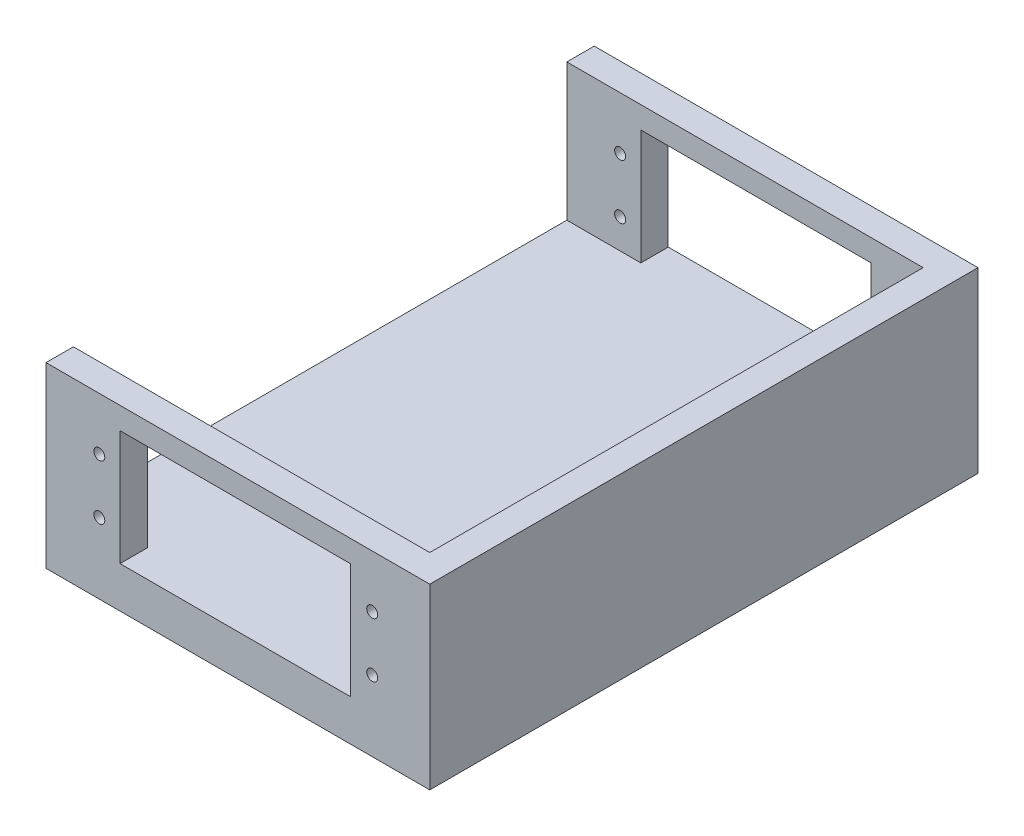
SolidWorks part; units mm, degrees
material "ABS"
ref_plane "Front Plane" through (0, 0, 0) normal (0, 0, 1) x (1, 0, 0)
ref_plane "Top Plane" through (0, 0, 0) normal (0, 1, 0) x (1, 0, 0)
ref_plane "Right Plane" through (0, 0, 0) normal (1, 0, 0) x (0, 0, -1)
sketch "Sketch1" plane through (0, 0, 0) normal (0, 1, 0) x (1, 0, 0)
  line L1 (0, 0) -> (70, 0)
  line L2 (0, 0) -> (0, 50)
  line L3 (0, 50) -> (70, 50)
  line L4 (70, 0) -> (70, 50)
  dimension "D1" = 70
  dimension "D2" = 50
extrude "Boss-Extrude1" add sketch "Sketch1" along normal blind 7.5
sketch "Sketch2" plane through (0, 7.5, 0) normal (0, 1, 0) x (1, 0, 0)
  line L0 (0, 50) -> (0, 0) construction
  line L1 (0, 0) -> (70, 0)
  line L2 (0, 0) -> (0, 5)
  line L3 (0, 5) -> (70, 5)
  line L4 (70, 0) -> (70, 5)
  line L5 (70, 0) -> (70, 50) construction
  line L6 (0, 0) -> (70, 0) construction
  dimension "D1" = 5
  dimension "D2" = 0
extrude "Boss-Extrude2" add sketch "Sketch2" along normal blind 25
sketch "Sketch3" plane through (0, 0, 0) normal (0, 0, 1) x (1, 0, 0)
  line L4 (13.5, 28.5) -> (55.5, 28.5)
  line L5 (13.5, 28.5) -> (13.5, 7.5)
  line L6 (13.5, 7.5) -> (55.5, 7.5)
  line L7 (55.5, 28.5) -> (55.5, 7.5)
  line L8 (0, 0) -> (70, 0) construction
  line L10 (70, 32.5) -> (70, 0) construction
  circle A4 centre (9.7208, 22.9) radius 1
  circle A5 centre (9.7208, 12.9) radius 1
  circle A6 centre (59.5, 12.9) radius 1
  circle A7 centre (59.5, 22.9) radius 1
  arc A8 (7.9104, 21.65) -> (7.9104, 24.15) centre (9.7208, 22.9) ccw construction
  dimension "D7" = 2
  dimension "D1" = 42
  dimension "D2" = 21
  dimension "D4" = 4
  dimension "D5" = 10
  dimension "D8" = 7.5
  dimension "D9" = 14.5
extrude "Cut-Extrude1" cut sketch "Sketch3" against normal blind 30
sketch "Sketch27" plane through (0, 0, -5) normal (0, 0, -1) x (-1, 0, 0)
  line L0 (-70, 32.5) -> (0, 32.5) construction
  line L1 (-70, 7.5) -> (-65, 7.5)
  line L2 (-70, 7.5) -> (-70, 32.5)
  line L3 (-70, 32.5) -> (-65, 32.5)
  line L4 (-65, 7.5) -> (-65, 32.5)
  dimension "D1" = 5
extrude "Boss-Extrude18" add sketch "Sketch27" along normal up to surface (45 mm away) up to face at (35, 3.75, -50)
ref_plane "Plane1" through (0, 0, -50) normal (0, 0, -1) x (0, -1, 0)
mirror "Mirror1" about plane through (0, 0, -50) normal (0, 0, -1) of "Boss-Extrude1", "Boss-Extrude2", "Cut-Extrude1", "Boss-Extrude18"
